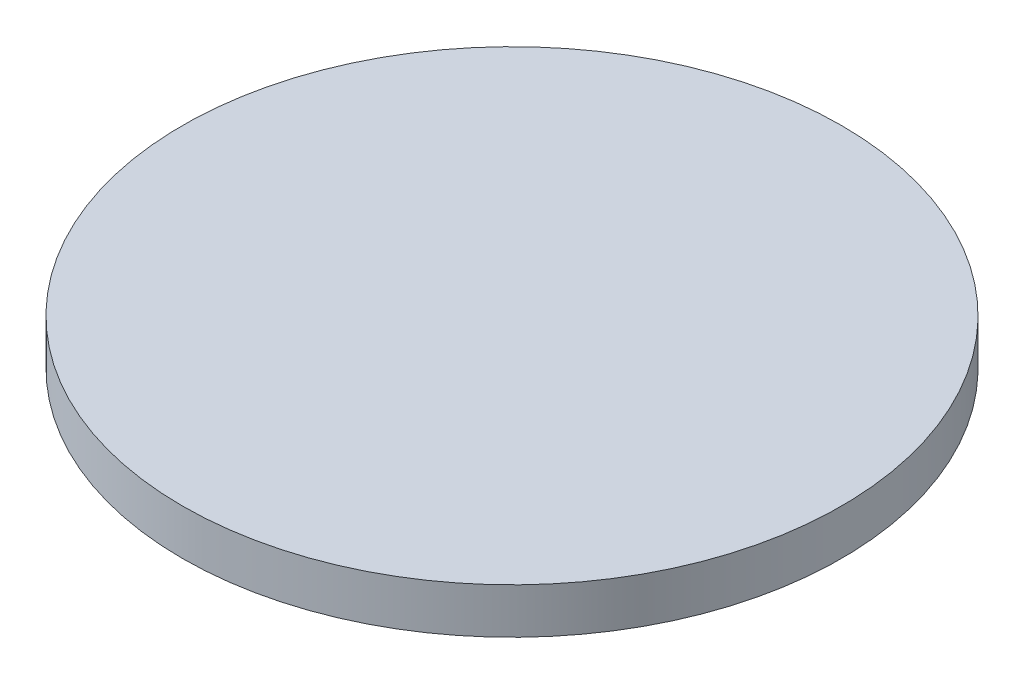
SolidWorks part; units mm, degrees
ref_plane "Alzado" through (0, 0, 0) normal (0, 0, 1) x (1, 0, 0)
ref_plane "Planta" through (0, 0, 0) normal (0, 1, 0) x (1, 0, 0)
ref_plane "Vista lateral" through (0, 0, 0) normal (1, 0, 0) x (0, 0, -1)
sketch "Croquis1" plane through (0, 0, 0) normal (0, 1, 0) x (1, 0, 0)
  circle A0 centre (0, 0) radius 36.25
  dimension "D1" = 72.5
extrude "Saliente-Extruir1" add sketch "Croquis1" along normal blind 5
